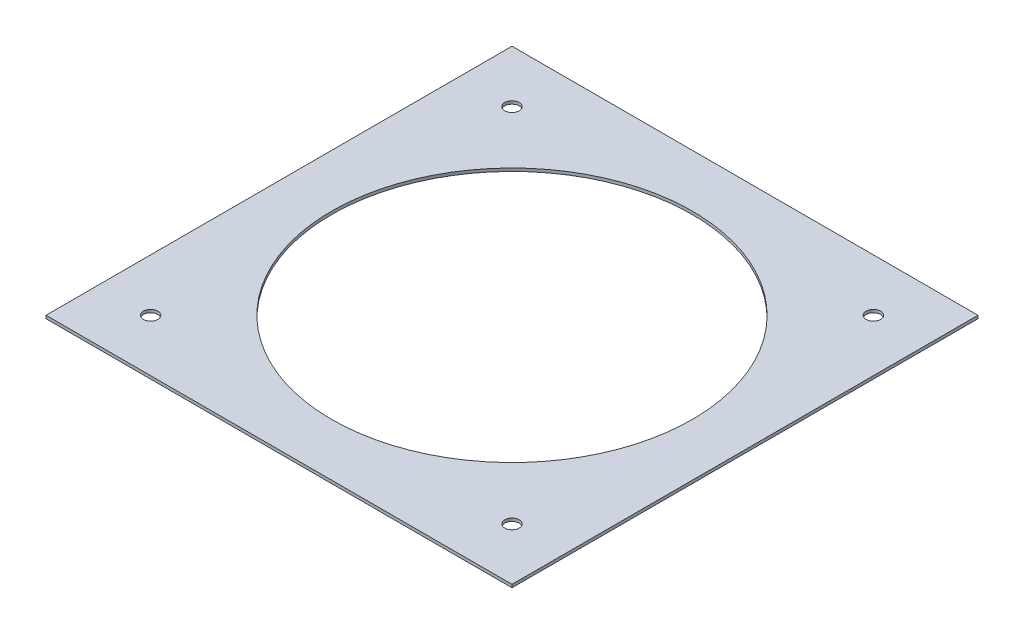
SolidWorks part; units mm, degrees
ref_plane "Front Plane" through (0, 0, 0) normal (0, 0, 1) x (1, 0, 0)
ref_plane "Top Plane" through (0, 0, 0) normal (0, 1, 0) x (1, 0, 0)
ref_plane "Right Plane" through (0, 0, 0) normal (1, 0, 0) x (0, 0, -1)
sketch "Sketch2" plane through (0, 0, 0) normal (0, 1, 0) x (1, 0, 0)
  line L0 (0, 21.246) -> (0, -18.4668) construction
  line L1 (-77.5, 77.5) -> (77.5, 77.5)
  line L2 (-77.5, 77.5) -> (-77.5, -77.5)
  line L3 (-77.5, -77.5) -> (77.5, -77.5)
  line L4 (77.5, 77.5) -> (77.5, -77.5)
  line L5 (-77.5, 77.5) -> (77.5, -77.5) construction
  line L6 (-77.5, -77.5) -> (77.5, 77.5) construction
  line L7 (-38.5405, 0) -> (45.5556, 0) construction
  circle A0 centre (0, 0) radius 109.6
  circle A1 centre (-60.1, -60.1) radius 2.4
  circle A2 centre (60.1, -60.1) radius 2.4
  circle A3 centre (60.1, 60.1) radius 2.4
  circle A4 centre (-60.1, 60.1) radius 2.4
  dimension "D1" = 219.2
  dimension "D5" = 4.8
  dimension "D2" = 155
  dimension "D3" = 155
  dimension "D4" = 17.4
extrude "Boss-Extrude1" add sketch "Sketch2" along normal blind 1 contours L3 A0 L4 L1 L2 A2 A1 A3 A4
sketch "Sketch3" plane through (0, 1, 0) normal (0, 1, 0) x (1, 0, 0)
  circle A0 centre (0, 0) radius 60
  dimension "D1" = 120
extrude "Cut-Extrude1" cut sketch "Sketch3" against normal blind 1 contours A0
